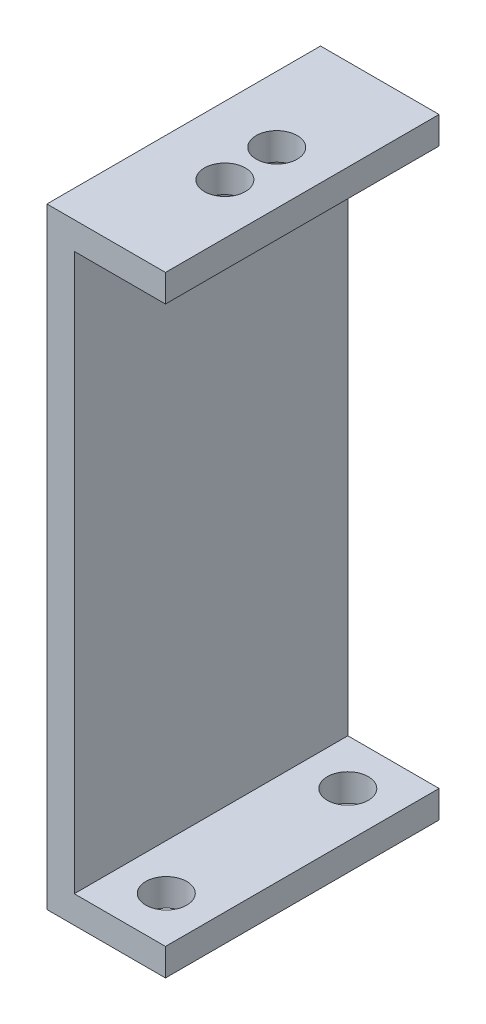
SolidWorks part; units mm, degrees
ref_plane "Front Plane" through (0, 0, 0) normal (0, 0, 1) x (1, 0, 0)
ref_plane "Top Plane" through (0, 0, 0) normal (0, 1, 0) x (1, 0, 0)
ref_plane "Right Plane" through (0, 0, 0) normal (1, 0, 0) x (0, 0, -1)
sketch "Sketch1" plane through (0, 0, 0) normal (0, 0, 1) x (1, 0, 0)
  line L1 (-6.5, -33.5) -> (6.5, -33.5)
  line L2 (-6.5, -33.5) -> (-6.5, 33.5)
  line L3 (-6.5, 33.5) -> (6.5, 33.5)
  line L4 (6.5, -33.5) -> (6.5, 33.5)
  line L5 (-6.5, -33.5) -> (6.5, 33.5) construction
  line L6 (-6.5, 33.5) -> (6.5, -33.5) construction
  point P0 (0, 0)
  dimension "D1" = 13
  dimension "D2" = 67
extrude "Boss-Extrude1" add sketch "Sketch1" along normal blind 30
sketch "Sketch2" plane through (6.5, 0, 0) normal (1, 0, 0) x (0, 0, -1)
  line L4 (-30, 33.5) -> (0, 33.5) construction
  line L5 (-30, -33.5) -> (0, -33.5) construction
  line L12 (22.1052, -30.5) -> (22.1052, 30.5)
  line L13 (22.1052, 30.5) -> (-45.3513, 30.5)
  line L14 (-45.3513, 30.5) -> (-45.3513, -30.5)
  line L15 (-45.3513, -30.5) -> (22.1052, -30.5)
  dimension "D1" = 3
  dimension "D2" = 3
extrude "Cut-Extrude1" cut sketch "Sketch2" against normal blind 10
hole_wizard "M4 Clearance Hole3" positions "Sketch4" profile "Sketch5" hole size "M4" standard "ANSI Metric"
sketch "Sketch4" plane through (0, 33.5, 0) normal (0, 1, 0) x (1, 0, 0)
  point P0 (0.7242, -12.0243)
sketch "Sketch5" plane through (0.7242, 33.5, 12.0243) normal (1, 0, 0) x (0, 0, 1)
  line L0 (0, 0) -> (0, 7.3519)
  line L1 (0, 7.3519) -> (2.25, 6)
  line L2 (2.25, 6) -> (2.25, 0)
  line L5 (2.25, 0) -> (0, 0)
  line L10 (0, 7.3519) -> (-2.25, 6) construction
  line L11 (0, -6.35) -> (0, 107.95) construction
  dimension "Hole Dia." = 4.5
  dimension "Hole Depth" = 6
  dimension "Drill Angle" = 118
hole_wizard "M4 Clearance Hole1" positions "Sketch7" profile "Sketch6" hole size "M4" standard "ANSI Metric"
sketch "Sketch7" plane through (0, -30.5, 0) normal (0, 1, 0) x (1, 0, 0)
  point P0 (1.5, -5.008)
  point P2 (1.5, -24.9107)
sketch "Sketch6" plane through (1.5, -30.5, 5.008) normal (1, 0, 0) x (0, 0, 1)
  line L0 (0, 0) -> (0, 7.3519)
  line L1 (0, 7.3519) -> (2.25, 6)
  line L2 (2.25, 6) -> (2.25, 0)
  line L5 (2.25, 0) -> (0, 0)
  line L10 (0, 7.3519) -> (-2.25, 6) construction
  line L11 (0, -6.35) -> (0, 107.95) construction
  dimension "Hole Dia." = 4.5
  dimension "Hole Depth" = 6
  dimension "Drill Angle" = 118
hole_wizard "M4 Clearance Hole2" positions "Sketch9" profile "Sketch8" hole size "M4" standard "ANSI Metric"
sketch "Sketch9" plane through (0, 33.5, 0) normal (0, 1, 0) x (1, 0, 0)
  point P5 (0.9582, -17.9447)
sketch "Sketch8" plane through (0.9582, 33.5, 17.9447) normal (1, 0, 0) x (0, 0, 1)
  line L0 (0, 0) -> (0, 7.3519)
  line L1 (0, 7.3519) -> (2.25, 6)
  line L2 (2.25, 6) -> (2.25, 0)
  line L5 (2.25, 0) -> (0, 0)
  line L10 (0, 7.3519) -> (-2.25, 6) construction
  line L11 (0, -6.35) -> (0, 107.95) construction
  dimension "Hole Dia." = 4.5
  dimension "Hole Depth" = 6
  dimension "Drill Angle" = 118
